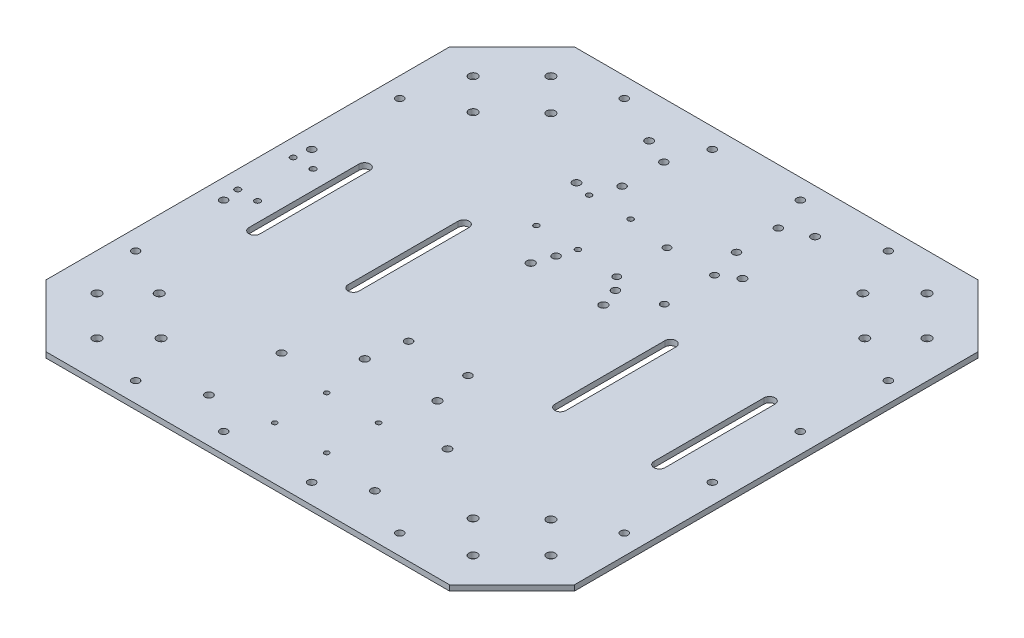
SolidWorks part; units mm, degrees
ref_plane "Front Plane" through (0, 0, 0) normal (0, 0, 1) x (1, 0, 0)
ref_plane "Top Plane" through (0, 0, 0) normal (0, 1, 0) x (1, 0, 0)
ref_plane "Right Plane" through (0, 0, 0) normal (1, 0, 0) x (0, 0, -1)
sketch "Sketch1" plane through (0, 0, 0) normal (0, 1, 0) x (1, 0, 0)
  line L0 (-61.766, 15.7353) -> (-25.845, 51.6564)
  line L1 (-61.766, 51.6564) -> (243.034, 51.6564)
  line L2 (-61.766, 51.6564) -> (-61.766, -253.1436)
  line L3 (-61.766, -253.1436) -> (243.034, -253.1436)
  line L4 (243.034, 51.6564) -> (243.034, -253.1436)
  line L5 (90.634, 95.069) -> (90.634, -294.9418) construction
  line L6 (-86.5248, -100.7436) -> (277.558, -100.7436) construction
  line L7 (243.034, 15.7353) -> (207.1129, 51.6564)
  line L8 (243.034, -217.2226) -> (207.1129, -253.1436)
  line L9 (-61.766, -217.2226) -> (-25.845, -253.1436)
  point P8 (90.634, 51.6564)
  point P11 (-61.766, -100.7436)
  dimension "D1" = 304.8
  dimension "D2" = 304.8
  dimension "D3" = 45
  dimension "D4" = 50.8
extrude "Boss-Extrude1" add sketch "Sketch1" along normal blind 3.175
sketch "Sketch2" plane through (0, 3.175, 0) normal (0, 1, 0) x (1, 0, 0)
  line L0 (-40.323, 7.7627) -> (-22.3625, -10.1978) construction
  line L1 (-17.8724, 30.2133) -> (0.6409, 11.7001) construction
  line L2 (-43.8055, 33.6958) -> (20.8232, -30.9329) construction
  line L3 (-61.766, 15.7353) -> (-25.845, 51.6564) construction
  line L7 (90.634, 51.6564) -> (90.634, -253.1436) construction
  line L8 (-25.845, 51.6564) -> (207.1129, 51.6564) construction
  line L9 (-25.845, -253.1436) -> (207.1129, -253.1436) construction
  line L10 (-61.766, -100.7436) -> (243.034, -100.7436) construction
  line L11 (-61.766, 15.7353) -> (-61.766, -217.2226) construction
  line L12 (243.034, 15.7353) -> (243.034, -217.2226) construction
  circle A0 centre (-17.8724, 30.2133) radius 2.4638
  circle A1 centre (0.6409, 11.7001) radius 2.4638
  circle A2 centre (-22.3625, -10.1978) radius 2.4638
  circle A3 centre (-40.323, 7.7627) radius 2.4638
  circle A4 centre (203.6304, -10.1978) radius 2.4638
  circle A5 centre (221.5909, 7.7627) radius 2.4638
  circle A6 centre (180.627, 11.7001) radius 2.4638
  circle A7 centre (199.1403, 30.2133) radius 2.4638
  circle A8 centre (-22.3625, -191.2895) radius 2.4638
  circle A9 centre (-40.323, -209.25) radius 2.4638
  circle A10 centre (-17.8724, -231.7006) radius 2.4638
  circle A11 centre (0.6409, -213.1873) radius 2.4638
  circle A12 centre (221.5909, -209.25) radius 2.4638
  circle A13 centre (199.1403, -231.7006) radius 2.4638
  circle A14 centre (180.627, -213.1873) radius 2.4638
  circle A15 centre (203.6304, -191.2895) radius 2.4638
  dimension "D3" = 4.9276
  dimension "D4" = 4.9276
  dimension "D5" = 4.9276
  dimension "D6" = 4.9276
  dimension "D1" = 25.4
  dimension "D2" = 31.75
  dimension "D7" = 15.875
extrude "Cut-Extrude1" cut sketch "Sketch2" against normal blind 6.35
sketch "Sketch3" plane through (0, 3.175, 0) normal (0, 1, 0) x (1, 0, 0)
  line L0 (-61.766, -100.7436) -> (278.5513, -100.7436) construction
  line L2 (-61.766, 15.7353) -> (-61.766, -217.2226) construction
  line L3 (90.634, 51.6564) -> (90.634, -273.1997) construction
  line L4 (-25.845, 51.6564) -> (207.1129, 51.6564) construction
  circle A0 centre (73.489, -58.1986) radius 2.159
  circle A1 centre (107.779, -58.1986) radius 2.159
  circle A2 centre (73.489, -143.2886) radius 2.159
  circle A3 centre (107.779, -143.2886) radius 2.159
  point P10 (-61.766, -100.7436)
  dimension "D3" = 4.318
  dimension "D4" = 4.318
  dimension "D5" = 4.318
  dimension "D6" = 4.318
  dimension "D1" = 34.29
  dimension "D2" = 85.09
  dimension "D7" = 42.545
  dimension "D8" = 17.145
extrude "Cut-Extrude2" cut sketch "Sketch3" against normal blind 6.35
sketch "Sketch4" plane through (0, 3.175, 0) normal (0, 1, 0) x (1, 0, 0)
  line L0 (90.634, 51.6564) -> (90.634, -36.4614) construction
  line L1 (-25.845, 51.6564) -> (207.1129, 51.6564) construction
  line L2 (-61.766, -100.7436) -> (257.447, -100.7436) construction
  line L3 (-61.766, 15.7353) -> (-61.766, -217.2226) construction
  circle A0 centre (42.755, 26.2564) radius 2.2225
  circle A1 centre (138.513, 26.2564) radius 2.2225
  circle A2 centre (42.755, -15.6536) radius 2.2225
  circle A3 centre (138.513, -15.6536) radius 2.2225
  circle A4 centre (138.513, -185.8336) radius 2.2225
  circle A5 centre (42.755, -185.8336) radius 2.2225
  circle A6 centre (138.513, -227.7436) radius 2.2225
  circle A7 centre (42.755, -227.7436) radius 2.2225
  circle A8 centre (69.679, -68.9936) radius 2.286
  circle A9 centre (111.589, -68.9936) radius 2.286
  circle A10 centre (69.679, -164.7516) radius 2.286
  circle A11 centre (111.589, -164.7516) radius 2.286
  point P32 (0, 0)
  point P33 (0, 0)
  point P34 (0, 0)
  dimension "D1" = 4.445
  dimension "D2" = 4.445
  dimension "D3" = 4.445
  dimension "D4" = 4.445
  dimension "D9" = 4.572
  dimension "D10" = 4.572
  dimension "D13" = 4.572
  dimension "D14" = 4.572
  dimension "D5" = 95.758
  dimension "D6" = 41.91
  dimension "D7" = 47.879
  dimension "D8" = 25.4
  dimension "D11" = 41.91
  dimension "D12" = 20.955
  dimension "D15" = 95.758
  dimension "D16" = 31.75
extrude "Cut-Extrude3" cut sketch "Sketch4" against normal through all
sketch "Sketch5" plane through (0, 3.175, 0) normal (0, 1, 0) x (1, 0, 0)
  line L0 (-61.766, -100.7436) -> (105.2484, -100.7436) construction
  line L1 (-61.766, 15.7353) -> (-61.766, -217.2226) construction
  circle A0 centre (-51.606, -84.7416) radius 1.651
  circle A1 centre (-40.176, -84.7416) radius 1.651
  circle A2 centre (-40.176, -116.7456) radius 1.651
  circle A3 centre (-51.606, -116.7456) radius 1.651
  dimension "D1" = 3.302
  dimension "D2" = 3.302
  dimension "D3" = 11.43
  dimension "D4" = 16.002
  dimension "D5" = 10.16
extrude "Cut-Extrude4" cut sketch "Sketch5" against normal through all
sketch "Sketch6" plane through (0, 3.175, 0) normal (0, 1, 0) x (1, 0, 0)
  line L0 (243.034, 15.7353) -> (243.034, -217.2226) construction
  line L1 (-25.845, 51.6564) -> (207.1129, 51.6564) construction
  line L2 (90.634, 51.6564) -> (90.634, -253.1436) construction
  line L3 (-25.845, -253.1436) -> (207.1129, -253.1436) construction
  line L4 (-61.766, 15.7353) -> (-61.766, -217.2226) construction
  circle A0 centre (101.302, -22.0036) radius 2.032
  circle A1 centre (101.302, -50.9596) radius 2.032
  circle A2 centre (128.734, -50.9596) radius 2.032
  circle A3 centre (128.734, -22.0036) radius 2.032
  circle A4 centre (57.614, 19.9064) radius 2.159
  circle A5 centre (57.614, -4.2236) radius 2.159
  circle A6 centre (123.654, -4.2236) radius 2.159
  circle A7 centre (123.654, 19.9064) radius 2.159
  circle A8 centre (75.648, -192.6916) radius 1.397
  circle A9 centre (75.648, -222.6636) radius 1.397
  circle A10 centre (105.62, -222.6636) radius 1.397
  circle A11 centre (105.62, -192.6916) radius 1.397
  circle A12 centre (52.534, -18.1936) radius 1.55
  circle A13 centre (52.534, -48.5936) radius 1.55
  circle A14 centre (76.534, -18.1936) radius 1.55
  circle A15 centre (76.534, -48.5936) radius 1.55
  dimension "D1" = 4.064
  dimension "D6" = 4.318
  dimension "D7" = 4.318
  dimension "D10" = 2.794
  dimension "D11" = 2.794
  dimension "D15" = 3.1
  dimension "D16" = 3.1
  dimension "D18" = 3.1
  dimension "D19" = 3.1
  dimension "D2" = 27.432
  dimension "D3" = 28.956
  dimension "D4" = 114.3
  dimension "D5" = 73.66
  dimension "D8" = 33.02
  dimension "D9" = 24.13
  dimension "D12" = 14.986
  dimension "D13" = 29.972
  dimension "D14" = 30.48
  dimension "D17" = 30.4
  dimension "D20" = 24
  dimension "D21" = 31.75
  dimension "D22" = 114.3
  dimension "D23" = 69.85
extrude "Cut-Extrude5" cut sketch "Sketch6" against normal through all
sketch "Sketch7" plane through (0, 3.175, 0) normal (0, 1, 0) x (1, 0, 0)
  line L0 (90.634, 51.6564) -> (90.634, -272.7763) construction
  line L1 (-25.845, 51.6564) -> (207.1129, 51.6564) construction
  line L2 (-61.766, -100.7436) -> (338.9555, -100.7436) construction
  line L3 (-61.766, 15.7353) -> (-61.766, -217.2226) construction
  circle A0 centre (65.234, 40.2264) radius 2.159
  circle A1 centre (14.434, 40.2264) radius 2.159
  circle A2 centre (-50.336, -75.3436) radius 2.159
  circle A3 centre (-50.336, -24.5436) radius 2.159
  circle A4 centre (231.604, -24.5436) radius 2.159
  circle A5 centre (231.604, -75.3436) radius 2.159
  circle A6 centre (166.834, 40.2264) radius 2.159
  circle A7 centre (116.034, 40.2264) radius 2.159
  circle A8 centre (116.034, -241.7136) radius 2.159
  circle A9 centre (166.834, -241.7136) radius 2.159
  circle A10 centre (231.604, -126.1436) radius 2.159
  circle A11 centre (231.604, -176.9436) radius 2.159
  circle A12 centre (-50.336, -176.9436) radius 2.159
  circle A13 centre (-50.336, -126.1436) radius 2.159
  circle A14 centre (14.434, -241.7136) radius 2.159
  circle A15 centre (65.234, -241.7136) radius 2.159
  dimension "D1" = 4.318
  dimension "D2" = 4.318
  dimension "D6" = 4.318
  dimension "D7" = 4.318
  dimension "D3" = 25.4
  dimension "D4" = 50.8
  dimension "D5" = 11.43
  dimension "D8" = 25.4
  dimension "D9" = 50.8
  dimension "D10" = 11.43
extrude "Cut-Extrude6" cut sketch "Sketch7" against normal through all
sketch "Sketch8" plane through (0, 3.175, 0) normal (0, 1, 0) x (1, 0, 0)
  line L0 (-26.206, -68.9936) -> (-26.206, -132.4936) construction
  line L1 (-23.031, -68.9936) -> (-23.031, -132.4936)
  line L2 (-29.381, -68.9936) -> (-29.381, -132.4936)
  line L3 (30.944, -68.9936) -> (30.944, -132.4936) construction
  line L4 (34.119, -68.9936) -> (34.119, -132.4936)
  line L5 (27.769, -68.9936) -> (27.769, -132.4936)
  line L7 (243.034, 15.7353) -> (243.034, -217.2226) construction
  line L8 (90.634, 51.6564) -> (90.634, -227.3263) construction
  line L9 (-25.845, 51.6564) -> (207.1129, 51.6564) construction
  line L10 (207.474, -68.9936) -> (207.474, -132.4936) construction
  line L11 (204.299, -68.9936) -> (204.299, -132.4936)
  line L12 (210.649, -68.9936) -> (210.649, -132.4936)
  line L13 (150.324, -68.9936) -> (150.324, -132.4936) construction
  line L14 (147.149, -68.9936) -> (147.149, -132.4936)
  line L15 (153.499, -68.9936) -> (153.499, -132.4936)
  arc A0 (-23.031, -68.9936) -> (-29.381, -68.9936) centre (-26.206, -68.9936) ccw
  arc A1 (-29.381, -132.4936) -> (-23.031, -132.4936) centre (-26.206, -132.4936) ccw
  arc A2 (34.119, -68.9936) -> (27.769, -68.9936) centre (30.944, -68.9936) ccw
  arc A3 (27.769, -132.4936) -> (34.119, -132.4936) centre (30.944, -132.4936) ccw
  arc A4 (204.299, -68.9936) -> (210.649, -68.9936) centre (207.474, -68.9936) cw
  arc A5 (210.649, -132.4936) -> (204.299, -132.4936) centre (207.474, -132.4936) cw
  arc A6 (147.149, -68.9936) -> (153.499, -68.9936) centre (150.324, -68.9936) cw
  arc A7 (153.499, -132.4936) -> (147.149, -132.4936) centre (150.324, -132.4936) cw
  point P2 (-26.206, -100.7436)
  point P7 (30.944, -100.7436)
  point P14 (90.634, -87.835)
  point P17 (243.034, -100.7436)
  point P24 (207.474, -100.7436)
  point P31 (150.324, -100.7436)
  dimension "D5" = 6.35
  dimension "D1" = 63.5
  dimension "D2" = 63.5
  dimension "D3" = 50.8
  dimension "D4" = 59.69
  dimension "D6" = 6.35
extrude "Cut-Extrude8" cut sketch "Sketch8" against normal through all
